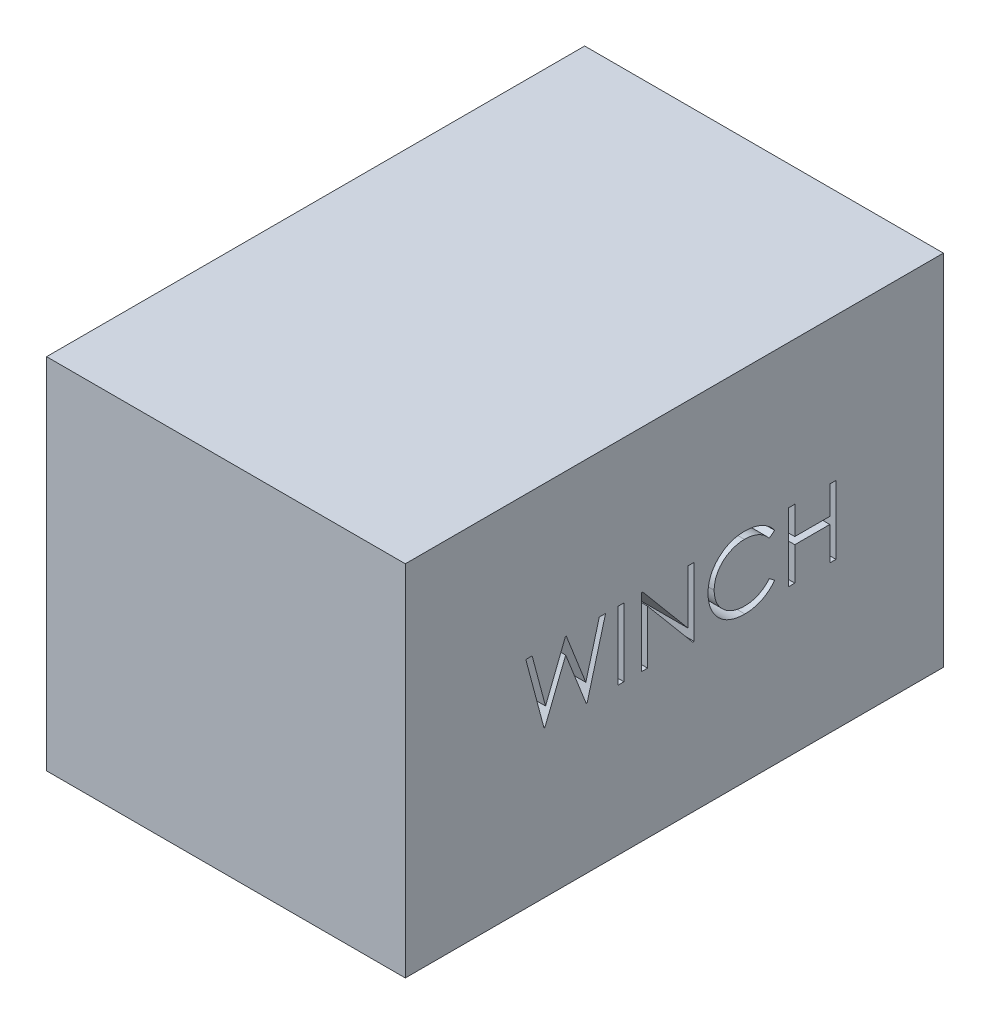
SolidWorks part; units mm, degrees
ref_plane "Front Plane" through (0, 0, 0) normal (0, 0, 1) x (1, 0, 0)
ref_plane "Top Plane" through (0, 0, 0) normal (0, 1, 0) x (1, 0, 0)
ref_plane "Right Plane" through (0, 0, 0) normal (1, 0, 0) x (0, 0, -1)
sketch "Sketch1" plane through (0, 0, 0) normal (0, 0, 1) x (1, 0, 0)
  line L1 (-55.5556, 57.8283) -> (44.4444, 57.8283)
  line L2 (-55.5556, 57.8283) -> (-55.5556, -42.1717)
  line L3 (-55.5556, -42.1717) -> (44.4444, -42.1717)
  line L4 (44.4444, 57.8283) -> (44.4444, -42.1717)
  dimension "D1" = 100
  dimension "D2" = 100
extrude "Boss-Extrude1" add sketch "Sketch1" along normal blind 150
sketch "Sketch2" plane through (44.4444, 0, 0) normal (1, 0, 0) x (0, 0, -1)
  text T0 "WINCH" font "Century Gothic" height in points 72
  point P1 (-114.1762, -12.3875)
  point P2 (-79.5134, 9.4573)
  point P3 (-52.7941, -21.2338)
  point P4 (-105.1494, -8.5963)
extrude "Cut-Extrude1" cut sketch "Sketch2" against normal blind 30
